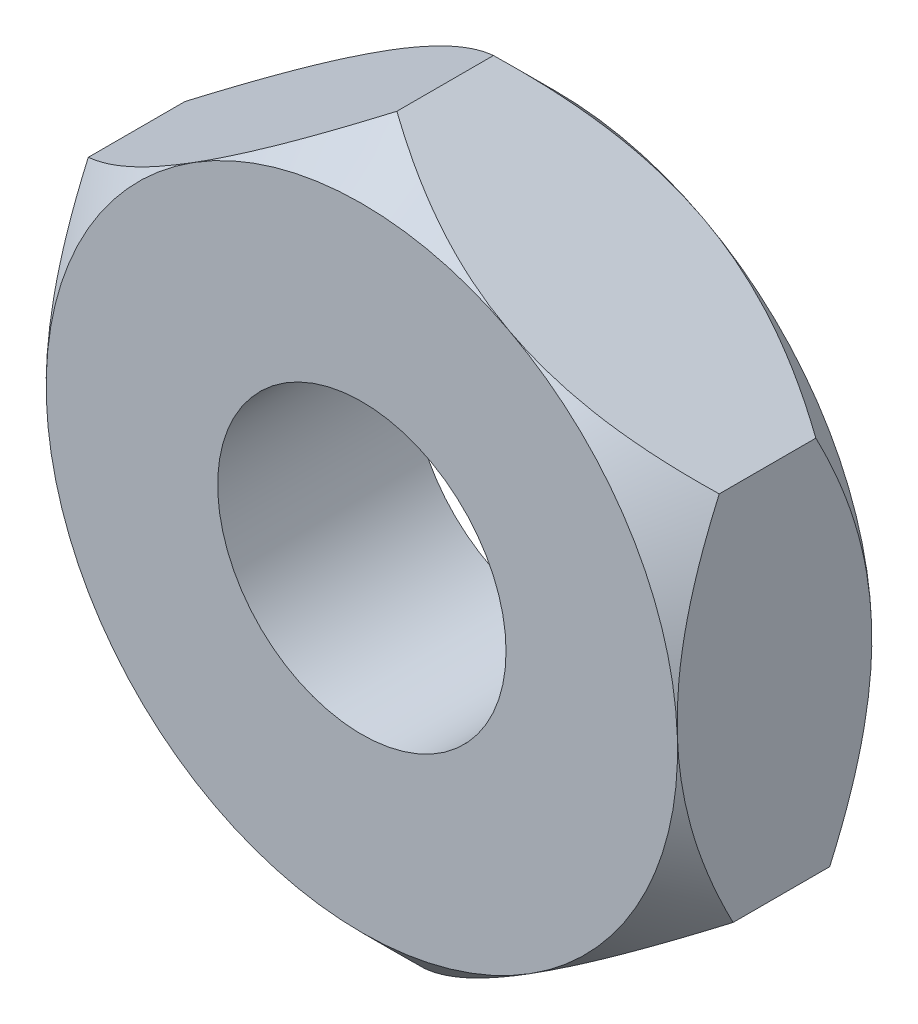
SolidWorks part; units mm, degrees
ref_plane "Front Plane" through (0, 0, 0) normal (0, 0, 1) x (1, 0, 0)
ref_plane "Top Plane" through (0, 0, 0) normal (0, 1, 0) x (1, 0, 0)
ref_plane "Right Plane" through (0, 0, 0) normal (1, 0, 0) x (0, 0, -1)
sketch "Sketch1" plane through (0, 0, 0) normal (0, 0, 1) x (1, 0, 0)
  line L1 (10.6203, -5.6051) -> (10.1643, 6.3949)
  line L2 (10.1643, 6.3949) -> (-0.4559, 12)
  line L3 (-0.4559, 12) -> (-10.6203, 5.6051)
  line L4 (-10.6203, 5.6051) -> (-10.1643, -6.3949)
  line L5 (-10.1643, -6.3949) -> (0.4559, -12)
  line L6 (0.4559, -12) -> (10.6203, -5.6051)
  circle A0 centre (0, 0) radius 4.75
  dimension "D2" = 9.5
  dimension "D1" = 12
extrude "Boss-Extrude1" add sketch "Sketch1" along normal mid plane 6.4 contours L5 L6 L1 L2 L3 L4 | A0
sketch "Sketch2" plane through (0, 0, 3.2) normal (0, 0, 1) x (1, 0, 0)
  line L0 (10.1643, 6.3949) -> (-0.4559, 12) construction
  circle A0 centre (0, 0) radius 10.3998
extrude "Cut-Extrude1" cut sketch "Sketch2" against normal blind 6.4 draft 45 flip side to cut
mirror "Mirror1" about plane through (0, 0, 0) normal (0, 0, 1) of "Cut-Extrude1"
